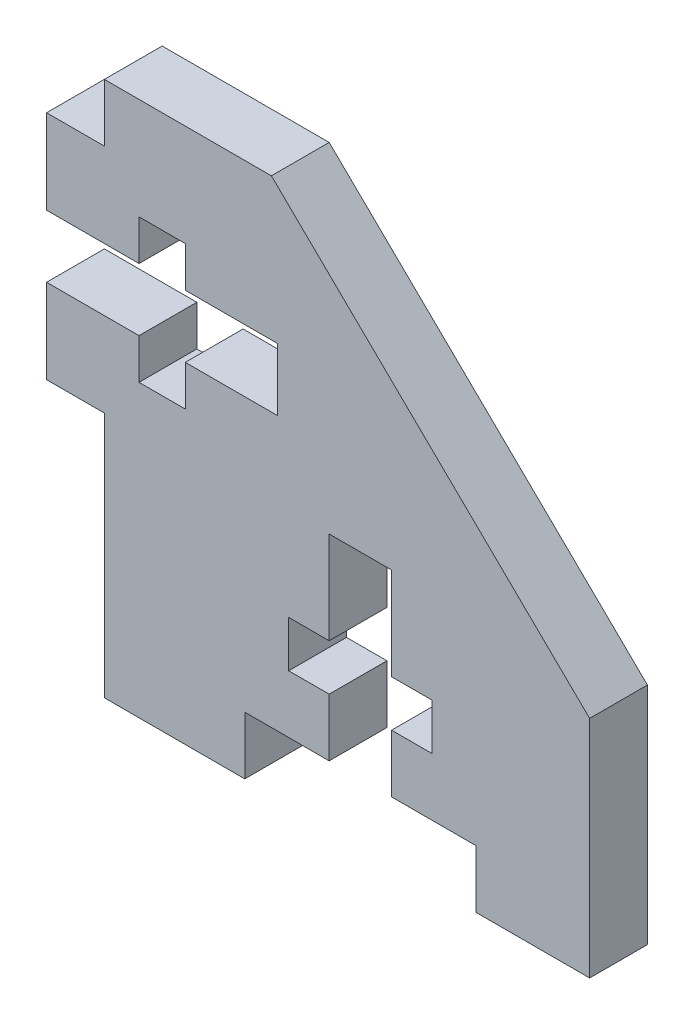
SolidWorks part; units mm, degrees
ref_plane "Front Plane" through (0, 0, 0) normal (0, 0, 1) x (1, 0, 0)
ref_plane "Top Plane" through (0, 0, 0) normal (0, 1, 0) x (1, 0, 0)
ref_plane "Right Plane" through (0, 0, 0) normal (1, 0, 0) x (0, 0, -1)
sketch "Sketch1" plane through (0, 0, 0) normal (0, 0, 1) x (1, 0, 0)
  line L0 (0, 0) -> (0, 4.6355)
  line L1 (0, 12.7) -> (3.175, 12.7)
  line L2 (3.175, 12.7) -> (3.175, 15.875)
  line L3 (3.175, 15.875) -> (12.351, 15.875)
  line L4 (29.8339, -10.373) -> (29.8339, -1.1969)
  line L5 (0, 0) -> (3.175, 0)
  line L6 (3.175, 0) -> (3.175, -10.373)
  line L7 (10.8892, -10.373) -> (15.5247, -10.373)
  line L8 (15.5247, -10.373) -> (15.5247, -7.198)
  line L9 (15.5247, -7.198) -> (13.3022, -7.198)
  line L10 (29.8339, -1.1969) -> (12.351, 15.875)
  line L11 (13.3022, -7.198) -> (13.3022, -4.658)
  line L12 (0, 6.35) -> (12.7, 6.35) construction
  line L13 (0, 8.0645) -> (5.08, 8.0645)
  line L14 (5.08, 8.0645) -> (5.08, 10.287)
  line L15 (5.08, 10.287) -> (7.62, 10.287)
  line L16 (7.62, 10.287) -> (7.62, 8.0645)
  line L17 (7.62, 8.0645) -> (12.7, 8.0645)
  line L18 (12.7, 8.0645) -> (12.7, 4.6355)
  line L19 (13.3022, -4.658) -> (15.5247, -4.658)
  line L20 (7.62, 4.6355) -> (12.7, 4.6355)
  line L21 (7.62, 2.413) -> (7.62, 4.6355)
  line L22 (5.08, 2.413) -> (7.62, 2.413)
  line L23 (5.08, 4.6355) -> (5.08, 2.413)
  line L24 (0, 4.6355) -> (5.08, 4.6355)
  line L25 (0, 8.0645) -> (0, 12.7)
  line L26 (15.5247, -4.658) -> (15.5247, 0.422)
  line L27 (15.5247, 0.422) -> (18.9537, 0.422)
  line L28 (18.9537, 0.422) -> (18.9537, -4.658)
  line L29 (18.9537, -4.658) -> (21.1762, -4.658)
  line L30 (21.1762, -4.658) -> (21.1762, -7.198)
  line L31 (21.1762, -7.198) -> (18.9537, -7.198)
  line L32 (18.9537, -7.198) -> (18.9537, -10.373)
  line L33 (18.9537, -10.373) -> (23.5892, -10.373)
  line L34 (29.8339, -10.373) -> (29.8339, -13.548)
  line L35 (29.8339, -13.548) -> (23.5892, -13.548)
  line L36 (23.5892, -13.548) -> (23.5892, -10.373)
  line L37 (15.5247, -10.373) -> (18.9537, -10.373) construction
  line L38 (3.175, -10.373) -> (3.175, -13.548)
  line L39 (3.175, -13.548) -> (10.8892, -13.548)
  line L40 (10.8892, -13.548) -> (10.8892, -10.373)
  point P39 (17.2392, -10.373)
  dimension "D8" = 2.54
  dimension "D1" = 12.7
  dimension "D2" = 3.175
  dimension "D3" = 5.08
  dimension "D4" = 1.7145
  dimension "D5" = 3.937
  dimension "D6" = 12.7
  dimension "D7" = 2.54
  dimension "D9" = 3.429
  dimension "D10" = 10.795
  dimension "D11" = 3.175
  dimension "D12" = 3.175
  dimension "D13" = 7.874
  dimension "D14" = 3.175
  dimension "D15" = 6.35
  dimension "D16" = 6.35
extrude "Boss-Extrude1" add sketch "Sketch1" along normal blind 3.175
